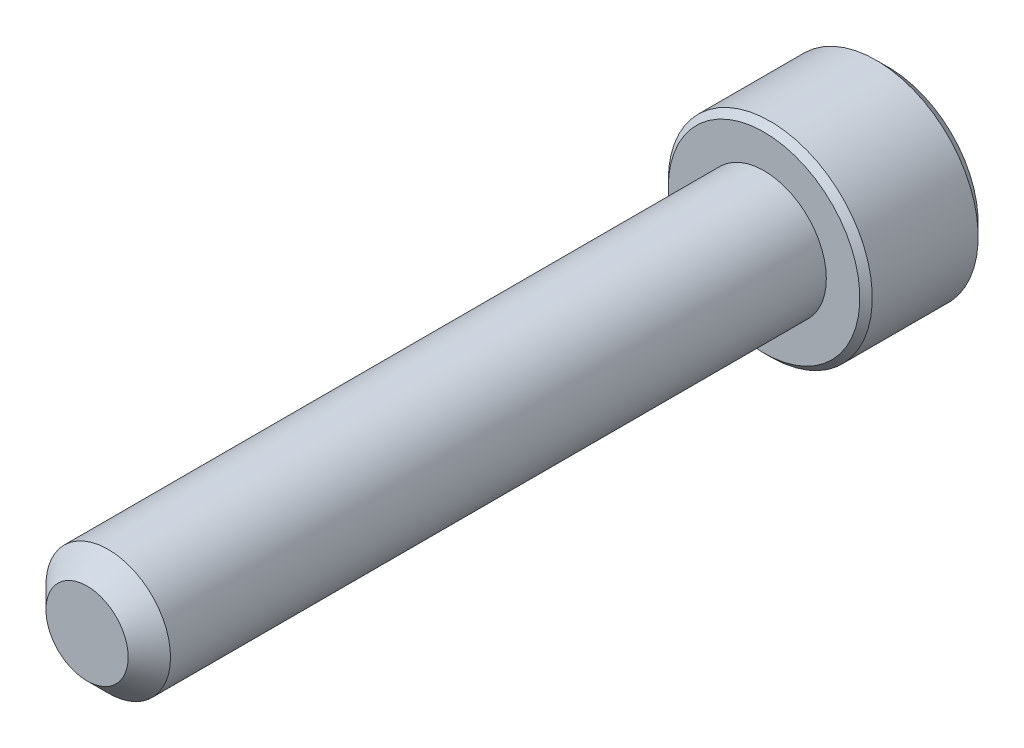
SolidWorks part; units mm, degrees
material "Plain Carbon Steel"
ref_plane "Front Plane" through (0, 0, 0) normal (0, 0, 1) x (1, 0, 0)
ref_plane "Top Plane" through (0, 0, 0) normal (0, 1, 0) x (1, 0, 0)
ref_plane "Right Plane" through (0, 0, 0) normal (1, 0, 0) x (0, 0, -1)
sketch "Sketch1" plane through (0, 0, 0) normal (0, 0, 1) x (1, 0, 0)
  line L0 (0, 1.7526) -> (0, -1.7526) construction
  circle A0 centre (0, 0) radius 1.7526
  dimension "OD" = 3.5052
extrude "Extrude1" add sketch "Sketch1" against normal blind 19.05
sketch "Sketch2" plane through (0, 0, 0) normal (0, 0, 1) x (1, 0, 0)
  circle A0 centre (0, 0) radius 1.7526 construction
  circle A1 centre (0, 0) radius 1.7526
curve "Helix/Spiral1" pitch 0.7937 height 19.8438 turns 25 parameters "pitch"=0.7937
chamfer "Chamfer3" distance 0.5953 angle 45 1 edges at (1.7526, 0, 0)
sketch "Sketch3" plane through (0, 0, 0) normal (1, 0, 0) x (0, 0, -1)
  line L0 (-0.6945, 1.7526) -> (-0.3969, 1.237)
  line L1 (-0.3969, 1.237) -> (-0.2977, 1.237)
  line L2 (-0.2977, 1.237) -> (0, 1.7526)
  line L3 (-0.6945, 1.7526) -> (0, 1.7526)
  line L4 (-0.3473, 1.7526) -> (-0.3473, 1.237) construction
  line L5 (-0.5457, 1.4948) -> (-0.1488, 1.4948) construction
  line L6 (0, 1.7526) -> (0, -1.7526) construction
  dimension "D1" = 0.0992
  dimension "D2" = 0.3969
  dimension "D3" = 60
sketch "Sketch6" plane through (0, 0, -19.05) normal (0, 0, -1) x (-1, 0, 0)
  circle A0 centre (0, 0) radius 2.8702
  dimension "head dia" = 5.7404
extrude "Extrude2" add sketch "Sketch6" along normal blind 3.5052
sketch "Sketch7" plane through (0, 0, -22.5552) normal (0, 0, -1) x (-1, 0, 0)
  line L1 (0, 1.604) -> (-1.3891, 0.802)
  line L2 (-1.3891, 0.802) -> (-1.3891, -0.802)
  line L3 (-1.3891, -0.802) -> (0, -1.604)
  line L4 (0, -1.604) -> (1.3891, -0.802)
  line L5 (1.3891, -0.802) -> (1.3891, 0.802)
  line L6 (1.3891, 0.802) -> (0, 1.604)
  circle A0 centre (0, 0) radius 1.3891 construction
  dimension "hex dia" = 2.7781
extrude "Cut-Extrude1" cut sketch "Sketch7" against normal blind 2.0836
sketch "Sketch8" plane through (0, 0, -22.5552) normal (0, 0, -1) x (-1, 0, 0)
  circle A0 centre (0, 0) radius 1.604
extrude "Cut-Extrude2" cut sketch "Sketch8" against normal blind 0.3505 draft 45
chamfer "Chamfer1" distance 0.3505 angle 45 1 edges at (-2.8702, 0, -22.5552)
chamfer "Chamfer2" distance 0.1753 angle 45 1 edges at (-2.8702, 0, -19.05)
sketch "Sketch9" plane through (0, 0, 0) normal (1, 0, 0) x (0, 0, -1)
  line L0 (0, 1.7526) -> (0, -1.7526) construction
  line L1 (4.3656, 1.7526) -> (4.3656, -1.7526) construction
  line L2 (19.05, 2.8702) -> (19.05, -2.8702) construction
  line L3 (22.5552, 2.8702) -> (22.5552, -2.8702) construction
  line L4 (22.5552, 0) -> (0, 0) construction
  dimension "D1" = 4.3656
  dimension "D2" = 3.5052
  dimension "D3" = 5.7404
  dimension "D4" = 19.05
equation "\"D3@Helix/Spiral1\" = \"screw length@Extrude1\"+\"pitch@Helix/Spiral1\""
equation "\"D1@Sketch3\" = \"pitch@Helix/Spiral1\"*.125"
equation "\"D2@Sketch3\" = \"pitch@Helix/Spiral1\"*.5"
equation "\"D1@Cut-Extrude1\" = \"hex dia@Sketch7\"*.75"
equation "\"D1@Chamfer1\" = \"head depth@Extrude2\"/10"
equation "\"D1@Sketch9\" = \"pitch@Helix/Spiral1\"*5.5"
equation "\"D1@Chamfer2\" = \"D1@Chamfer1\"/2"
equation "\"D1@Cut-Extrude2\" = \"D1@Chamfer2\"*2"
equation "\"D1@Chamfer3\" = \"pitch@Helix/Spiral1\"*.750"
equation "\"D2@Sketch9\" = \"head depth@Extrude2\""
equation "\"D3@Sketch9\" = \"head dia@Sketch6\""
equation "\"D4@Sketch9\" = \"screw length@Extrude1\""
